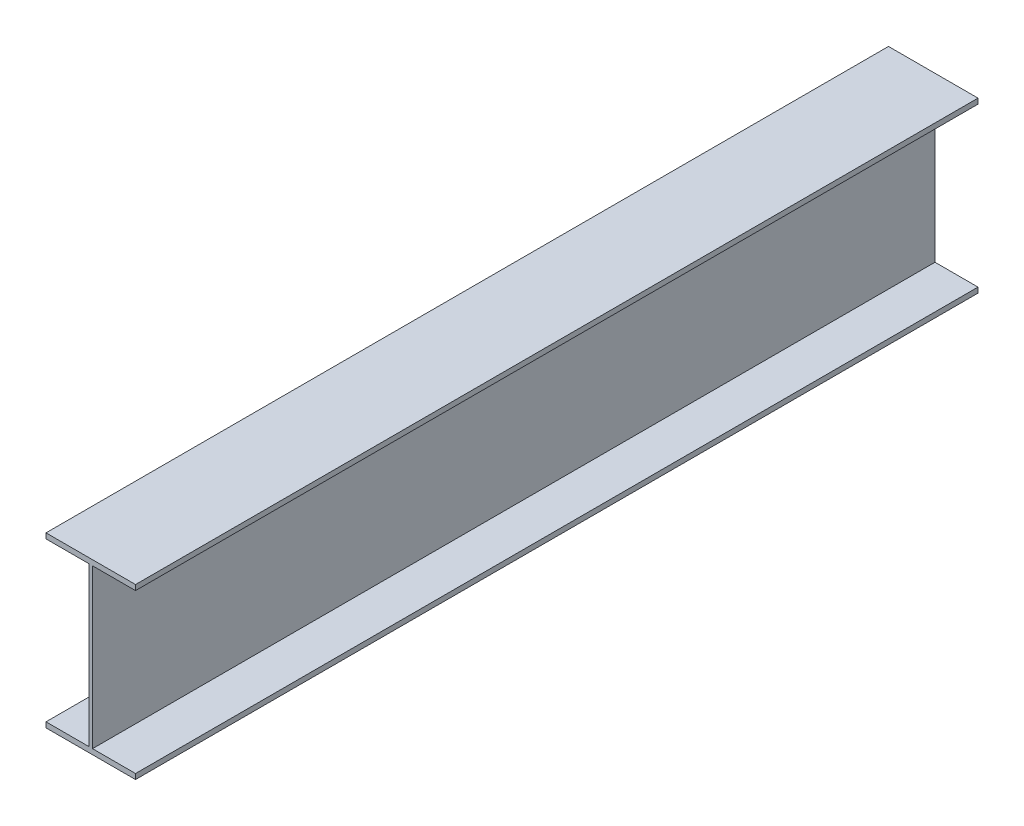
SolidWorks part; units mm, degrees
material "ASTM A36 Steel"
ref_plane "Front Plane" through (0, 0, 0) normal (0, 0, 1) x (1, 0, 0)
ref_plane "Top Plane" through (0, 0, 0) normal (0, 1, 0) x (1, 0, 0)
ref_plane "Right Plane" through (0, 0, 0) normal (1, 0, 0) x (0, 0, -1)
sketch "Sketch1" plane through (0, 0, 0) normal (0, 0, 1) x (1, 0, 0)
  line L0 (-161.925, 305.562) -> (-161.925, 286.512)
  line L1 (-161.925, -305.562) -> (161.925, -305.562)
  line L2 (-161.925, -305.562) -> (-161.925, 305.562)
  line L3 (-161.925, 305.562) -> (161.925, 305.562)
  line L4 (161.925, -305.562) -> (161.925, 305.562)
  line L5 (-161.925, -305.562) -> (161.925, 305.562) construction
  line L6 (-161.925, 305.562) -> (161.925, -305.562) construction
  line L7 (-161.925, 305.562) -> (161.925, 305.562)
  line L8 (-6.35, -305.562) -> (6.35, -305.562)
  line L9 (-6.35, -286.512) -> (-6.35, 286.512)
  line L10 (-6.35, 305.562) -> (6.35, 305.562)
  line L11 (6.35, -286.512) -> (6.35, 286.512)
  line L12 (-6.35, -305.562) -> (6.35, 305.562) construction
  line L13 (-6.35, 305.562) -> (6.35, -305.562) construction
  line L14 (-161.925, 305.562) -> (-161.925, 286.512)
  line L15 (161.925, 305.562) -> (161.925, 286.512)
  line L16 (-161.925, 286.512) -> (-5.9541, 286.512)
  line L17 (-161.925, -305.562) -> (161.925, -305.562)
  line L18 (-161.925, -305.562) -> (-161.925, -286.512)
  line L19 (161.925, -305.562) -> (161.925, -286.512)
  line L20 (-161.925, -286.512) -> (-5.9541, -286.512)
  line L21 (5.9541, 286.512) -> (161.925, 286.512)
  line L22 (5.9541, -286.512) -> (161.925, -286.512)
  point P0 (0, 0)
  point P8 (0, 0)
  dimension "D1" = 611.124
  dimension "D2" = 323.85
  dimension "D3" = 12.7
  dimension "D4" = 19.05
  dimension "D5" = 19.05
extrude "Boss-Extrude1" add sketch "Sketch1" along normal blind 3048
ref_point "Point1"
